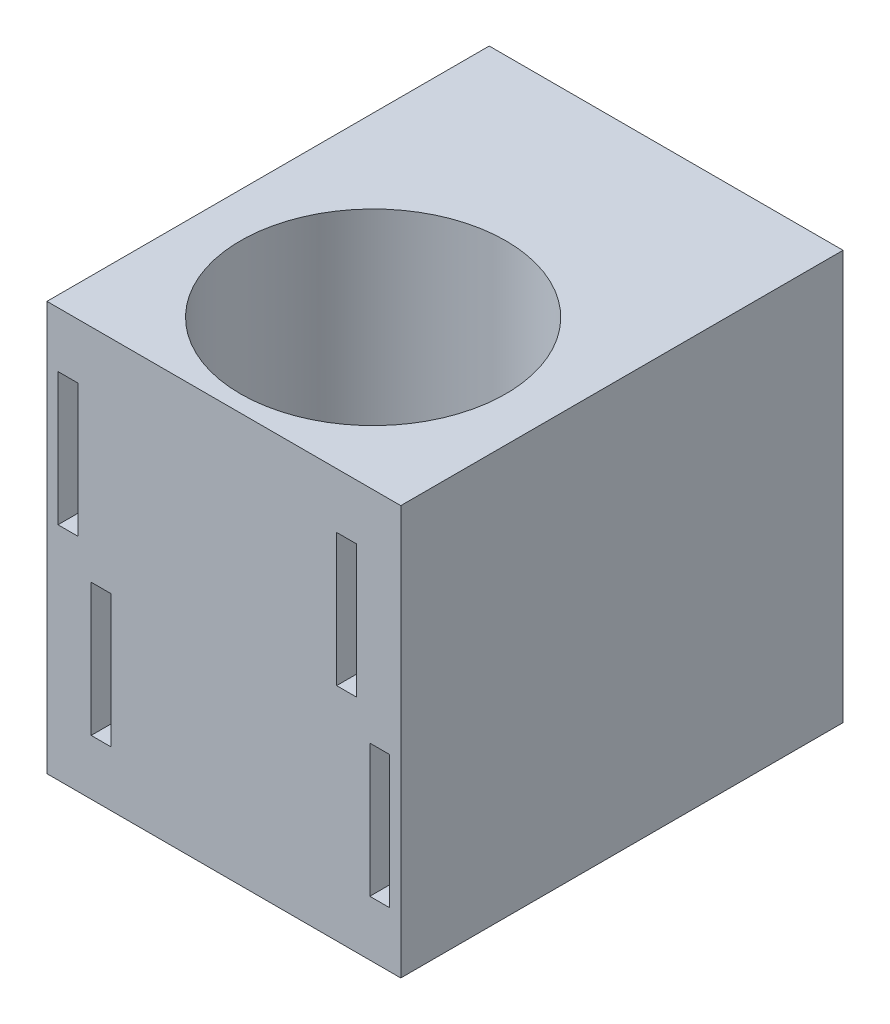
SolidWorks part; units mm, degrees
ref_plane "Front Plane" through (0, 0, 0) normal (0, 0, 1) x (1, 0, 0)
ref_plane "Top Plane" through (0, 0, 0) normal (0, 1, 0) x (1, 0, 0)
ref_plane "Right Plane" through (0, 0, 0) normal (1, 0, 0) x (0, 0, -1)
sketch "Sketch1" plane through (0, 0, 0) normal (0, 1, 0) x (1, 0, 0)
  line L0 (-12, 0) -> (-16, 0) construction
  line L1 (16, 13.5) -> (-16, 13.5)
  line L2 (16, 13.5) -> (16, -13.5)
  line L3 (16, -13.5) -> (-16, -13.5)
  line L4 (-16, 13.5) -> (-16, -13.5)
  line L5 (0, 12) -> (0, 13.5) construction
  line L6 (0, -12) -> (0, -13.5) construction
  line L7 (12, 0) -> (16, 0) construction
  circle A0 centre (0, 0) radius 12
  dimension "D1" = 24
  dimension "D2" = 32
  dimension "D3" = 27
extrude "Boss-Extrude1" add sketch "Sketch1" along normal blind 30
sketch "Sketch3" plane through (0, 0, 13.5) normal (0, 0, 1) x (1, 0, 0)
  line L0 (-12, 1.5) -> (-16, 1.5) construction
  line L1 (-12, 1.5) -> (-10.2, 1.5)
  line L2 (-12, 1.5) -> (-12, 13.5)
  line L3 (-12, 13.5) -> (-10.2, 13.5)
  line L4 (-10.2, 1.5) -> (-10.2, 13.5)
  line L5 (10.2, 28.5) -> (12, 28.5)
  line L6 (10.2, 28.5) -> (10.2, 16.5)
  line L7 (10.2, 16.5) -> (12, 16.5)
  line L8 (12, 28.5) -> (12, 16.5)
  line L9 (-16, 30) -> (-16, 0) construction
  line L10 (12, 16.5) -> (16, 16.5) construction
  line L11 (16, 30) -> (16, 0) construction
  line L13 (-10.2, 1.5) -> (-10.2, 0) construction
  line L14 (10.2, 28.5) -> (10.2, 30) construction
  line L15 (-16, 0) -> (16, 0) construction
  line L16 (-16, 30) -> (16, 30) construction
  point P8 (0, 0)
  dimension "D1" = 10.2
  dimension "D2" = 1.8
  dimension "D3" = 1.5
  dimension "D4" = 12
extrude "Cut-Extrude1" cut sketch "Sketch3" against normal blind 13.5
sketch "Sketch4" plane through (0, 0, 13.5) normal (0, 0, 1) x (1, 0, 0)
  line L0 (-16, 30) -> (-16, 0) construction
  line L1 (-15, 28.5) -> (-13.2, 28.5)
  line L2 (-15, 28.5) -> (-15, 16.5)
  line L3 (-15, 16.5) -> (-13.2, 16.5)
  line L4 (-13.2, 28.5) -> (-13.2, 16.5)
  line L5 (13.2, 13.5) -> (15, 13.5)
  line L6 (13.2, 13.5) -> (13.2, 1.5)
  line L7 (13.2, 1.5) -> (15, 1.5)
  line L8 (15, 13.5) -> (15, 1.5)
  line L9 (-15, 16.5) -> (-16, 16.5) construction
  line L10 (15, 13.5) -> (16, 13.5) construction
  line L11 (16, 30) -> (16, 0) construction
  line L12 (15, 1.5) -> (15, 0) construction
  line L13 (-16, 0) -> (16, 0) construction
  line L14 (-15, 28.5) -> (-15, 30) construction
  line L15 (-16, 30) -> (16, 30) construction
  dimension "D1" = 1.8
  dimension "D2" = 1
  dimension "D3" = 12
  dimension "D4" = 1.5
extrude "Cut-Extrude2" cut sketch "Sketch4" against normal through all
sketch "Sketch5" plane through (0, 0, -13.5) normal (0, 0, -1) x (-1, 0, 0)
  line L0 (15, 16.5) -> (13.2, 16.5) construction
  line L1 (15, 16.5) -> (13.2, 16.5)
  line L2 (13.2, 28.5) -> (15, 28.5) construction
  line L3 (13.2, 28.5) -> (15, 28.5)
  line L4 (-16, 0) -> (16, 0)
  line L5 (16, 0) -> (16, 30)
  line L6 (16, 30) -> (-16, 30)
  line L7 (-16, 30) -> (-16, 0)
  line L8 (-16, 0) -> (16, 0)
  line L9 (16, 0) -> (16, 30)
  line L10 (16, 30) -> (-16, 30)
  line L11 (-16, 30) -> (-16, 0)
  line L12 (15, 28.5) -> (15, 16.5) construction
  line L13 (15, 28.5) -> (15, 16.5)
  line L14 (13.2, 16.5) -> (13.2, 28.5) construction
  line L15 (13.2, 16.5) -> (13.2, 28.5)
  line L16 (-13.2, 13.5) -> (-13.2, 1.5) construction
  line L17 (-13.2, 13.5) -> (-13.2, 1.5)
  line L18 (-15, 13.5) -> (-13.2, 13.5) construction
  line L19 (-15, 13.5) -> (-13.2, 13.5)
  line L20 (-15, 1.5) -> (-15, 13.5) construction
  line L21 (-15, 1.5) -> (-15, 13.5)
  line L22 (-13.2, 1.5) -> (-15, 1.5) construction
  line L23 (-13.2, 1.5) -> (-15, 1.5)
  dimension "D1" = 0
extrude "Boss-Extrude2" add sketch "Sketch5" along normal blind 13
sketch "Sketch6" plane through (0, 30, 0) normal (0, 1, 0) x (1, 0, 0)
  line L4 (-16, 26.5) -> (-16, -13.5)
  line L5 (-16, -13.5) -> (16, -13.5)
  line L6 (16, -13.5) -> (16, 26.5)
  line L7 (16, 26.5) -> (-16, 26.5)
  line L8 (-16, 26.5) -> (-16, -13.5)
  line L9 (-16, -13.5) -> (16, -13.5)
  line L10 (16, -13.5) -> (16, 26.5)
  line L11 (16, 26.5) -> (-16, 26.5)
  circle A0 centre (0, 0) radius 12 construction
  circle A1 centre (0, 0) radius 12
  dimension "D1" = 0
extrude "Boss-Extrude3" add sketch "Sketch6" along normal blind 3.5
sketch "Sketch7" plane through (0, 0, 0) normal (0, -1, 0) x (1, 0, 0)
  line L4 (-16, 13.5) -> (-16, -26.5)
  line L5 (-16, -26.5) -> (16, -26.5)
  line L6 (16, -26.5) -> (16, 13.5)
  line L7 (16, 13.5) -> (-16, 13.5)
  line L8 (-16, 13.5) -> (-16, -26.5)
  line L9 (-16, -26.5) -> (16, -26.5)
  line L10 (16, -26.5) -> (16, 13.5)
  line L11 (16, 13.5) -> (-16, 13.5)
  circle A0 centre (0, 0) radius 12 construction
  circle A1 centre (0, 0) radius 12
  dimension "D1" = 0
extrude "Boss-Extrude4" add sketch "Sketch7" along normal blind 3.5
